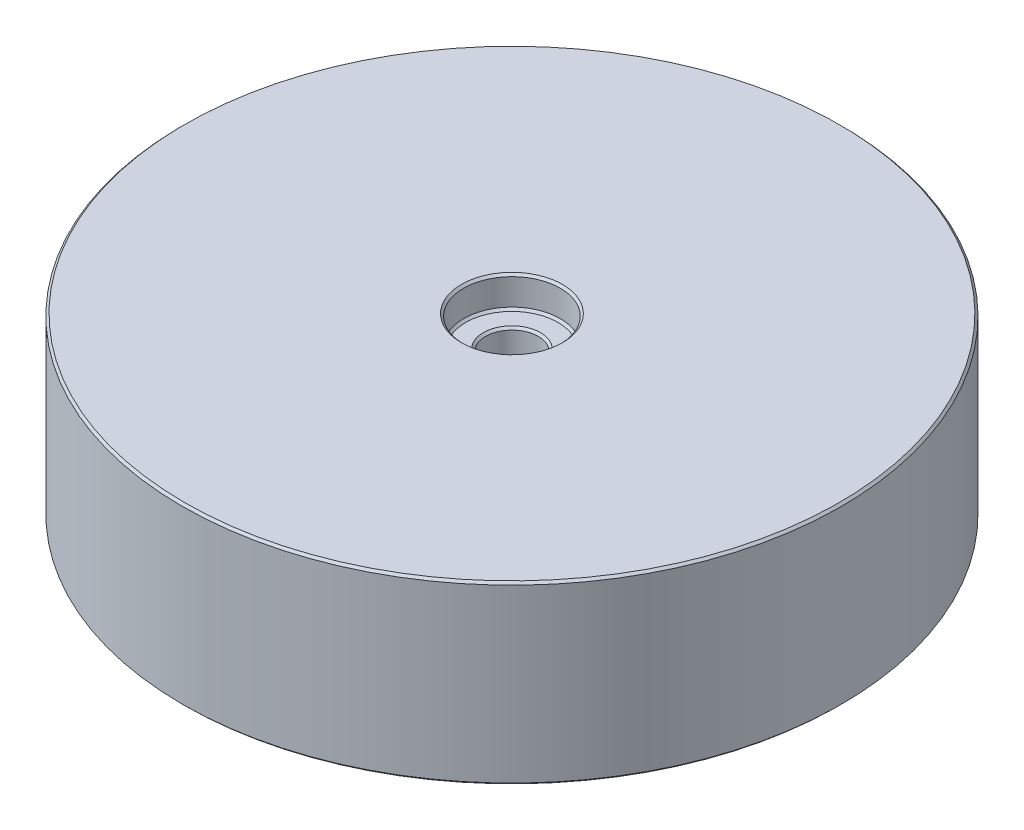
SolidWorks part; units mm, degrees
ref_plane "Front Plane" through (0, 0, 0) normal (0, 0, 1) x (1, 0, 0)
ref_plane "Top Plane" through (0, 0, 0) normal (0, 1, 0) x (1, 0, 0)
ref_plane "Right Plane" through (0, 0, 0) normal (1, 0, 0) x (0, 0, -1)
sketch "Sketch2" plane through (0, 0, 0) normal (1, 0, 0) x (0, 0, -1)
  line L0 (0, 77.6219) -> (0, -63.2806) construction
  line L1 (-6, 12.5) -> (-6, -12.5)
  line L2 (-11.5, -20) -> (-36.5, -20)
  line L3 (-37, -19.5) -> (-37, -10.5)
  line L4 (-37.5, -10) -> (-71.5, -10)
  line L5 (-72, -10.5) -> (-72, -19.5)
  line L6 (-72.5, -20) -> (-74.5, -20)
  line L7 (-75, -19.5) -> (-75, 19.5)
  line L8 (-74.5, 20) -> (-72.5, 20)
  line L9 (-72, 19.5) -> (-72, 10.5) construction
  line L10 (-71.5, 10) -> (-37.5, 10) construction
  line L11 (-37, 10.5) -> (-37, 19.5) construction
  line L12 (-36.5, 20) -> (-11.5, 20)
  line L13 (0, 0) -> (-86.9978, 0) construction
  line L14 (-6, -19.5) -> (-6.5, -20) construction
  line L15 (-6.5, 20) -> (-6, 19.5) construction
  line L16 (-36.5, -20) -> (-37, -19.5)
  line L17 (-37, 19.5) -> (-36.5, 20) construction
  line L18 (-72.5, 20) -> (-72, 19.5) construction
  line L19 (-72, 10.5) -> (-71.5, 10) construction
  line L20 (-37.5, 10) -> (-37, 10.5) construction
  line L21 (-75, 19.5) -> (-74.5, 20)
  line L22 (-74.5, -20) -> (-75, -19.5)
  line L23 (-72, -19.5) -> (-72.5, -20)
  line L24 (-71.5, -10) -> (-72, -10.5)
  line L25 (-37, -10.5) -> (-37.5, -10)
  line L26 (-11, 19.5) -> (-11, 13.5)
  line L27 (-10.5, 13) -> (-6.5, 13)
  line L28 (-6, 19.5) -> (-6, 13) construction
  line L29 (-11, 20) -> (-6.5, 20) construction
  line L30 (-10.5, -13) -> (-6.5, -13)
  line L31 (-11, -19.5) -> (-11, -13.5)
  line L32 (-6.5, -20) -> (-11, -20) construction
  line L33 (-6, -13) -> (-6, -19.5) construction
  line L34 (-6, -12.5) -> (-6.5, -13)
  line L35 (-11, -13.5) -> (-10.5, -13)
  line L36 (-11, -19.5) -> (-11.5, -20)
  line L37 (-11.5, 20) -> (-11, 19.5)
  line L38 (-11, 13.5) -> (-10.5, 13)
  line L39 (-6.5, 13) -> (-6, 12.5)
  line L40 (-72.5, 20) -> (-37, 20)
  line L41 (-37, 20) -> (-36.5, 20)
  point P2 (-6, 20)
  point P4 (-6, -20)
  point P6 (-37, -20)
  point P7 (-37, -10)
  point P8 (-72, -10)
  point P9 (-72, -20)
  point P10 (-75, -20)
  point P11 (-75, 20)
  point P12 (-72, 20)
  point P13 (-72, 10)
  point P14 (-37, 10)
  point P15 (-37, 20)
  point P42 (-11, 13)
  point P43 (-11, -13)
  dimension "D1" = 150
  dimension "D2" = 12
  dimension "D3" = 10
  dimension "D4" = 3
  dimension "D5" = 35
  dimension "D6" = 10
  dimension "D7" = 40
  dimension "D8" = 22
  dimension "D9" = 7
revolve "Revolve1" add sketch "Sketch2" angle 360 about L0
sketch "Sketch3" plane through (0, -10, 0) normal (0, -1, 0) x (1, 0, 0)
  line L0 (0, 0) -> (0, 79.0098) construction
  line L1 (41.0122, 55.8614) -> (20.5061, 35.3553) construction
  line L2 (-9.5, 69.5) -> (9.5, 69.5) construction
  line L3 (-10.5, 68.5) -> (-10.5, 39.5) construction
  line L4 (-9.5, 38.5) -> (9.5, 38.5) construction
  line L5 (10.5, 68.5) -> (10.5, 39.5) construction
  line L6 (-10.5, 69.5) -> (10.5, 38.5) construction
  line L7 (-10.5, 38.5) -> (10.5, 69.5) construction
  line L8 (42.4264, 55.8614) -> (55.8614, 42.4264) construction
  line L9 (55.8614, 41.0122) -> (35.3553, 20.5061) construction
  line L10 (20.5061, 33.9411) -> (33.9411, 20.5061) construction
  line L11 (68.5, 10.5) -> (39.5, 10.5) construction
  line L12 (69.5, 9.5) -> (69.5, -9.5) construction
  line L13 (68.5, -10.5) -> (39.5, -10.5) construction
  line L14 (38.5, 9.5) -> (38.5, -9.5) construction
  line L15 (55.8614, -41.0122) -> (35.3553, -20.5061) construction
  line L16 (55.8614, -42.4264) -> (42.4264, -55.8614) construction
  line L17 (41.0122, -55.8614) -> (20.5061, -35.3553) construction
  line L18 (33.9411, -20.5061) -> (20.5061, -33.9411) construction
  line L19 (10.5, -68.5) -> (10.5, -39.5) construction
  line L20 (9.5, -69.5) -> (-9.5, -69.5) construction
  line L21 (-10.5, -68.5) -> (-10.5, -39.5) construction
  line L22 (9.5, -38.5) -> (-9.5, -38.5) construction
  line L23 (-41.0122, -55.8614) -> (-20.5061, -35.3553) construction
  line L24 (-42.4264, -55.8614) -> (-55.8614, -42.4264) construction
  line L25 (-55.8614, -41.0122) -> (-35.3553, -20.5061) construction
  line L26 (-20.5061, -33.9411) -> (-33.9411, -20.5061) construction
  line L27 (-68.5, -10.5) -> (-39.5, -10.5) construction
  line L28 (-69.5, -9.5) -> (-69.5, 9.5) construction
  line L29 (-68.5, 10.5) -> (-39.5, 10.5) construction
  line L30 (-38.5, -9.5) -> (-38.5, 9.5) construction
  line L31 (-55.8614, 41.0122) -> (-35.3553, 20.5061) construction
  line L32 (-55.8614, 42.4264) -> (-42.4264, 55.8614) construction
  line L33 (-41.0122, 55.8614) -> (-20.5061, 35.3553) construction
  line L34 (-33.9411, 20.5061) -> (-20.5061, 33.9411) construction
  line L35 (0, 0) -> (0, 93.1932) construction
  circle A0 centre (0, 0) radius 71 construction
  circle A1 centre (0, 0) radius 71.5 construction
  circle A2 centre (0, 0) radius 38 construction
  circle A3 centre (0, 0) radius 37.5 construction
  arc A4 (10.5, 39.5) -> (9.5, 38.5) centre (9.5, 39.5) cw construction
  arc A5 (-10.5, 39.5) -> (-9.5, 38.5) centre (-9.5, 39.5) ccw construction
  arc A6 (10.5, 68.5) -> (9.5, 69.5) centre (9.5, 68.5) ccw construction
  arc A7 (-10.5, 68.5) -> (-9.5, 69.5) centre (-9.5, 68.5) cw construction
  arc A8 (41.0122, 55.8614) -> (42.4264, 55.8614) centre (41.7193, 55.1543) cw construction
  arc A9 (20.5061, 35.3553) -> (20.5061, 33.9411) centre (21.2132, 34.6482) ccw construction
  arc A10 (55.8614, 41.0122) -> (55.8614, 42.4264) centre (55.1543, 41.7193) ccw construction
  arc A11 (35.3553, 20.5061) -> (33.9411, 20.5061) centre (34.6482, 21.2132) cw construction
  arc A12 (68.5, 10.5) -> (69.5, 9.5) centre (68.5, 9.5) cw construction
  arc A13 (39.5, 10.5) -> (38.5, 9.5) centre (39.5, 9.5) ccw construction
  arc A14 (68.5, -10.5) -> (69.5, -9.5) centre (68.5, -9.5) ccw construction
  arc A15 (39.5, -10.5) -> (38.5, -9.5) centre (39.5, -9.5) cw construction
  arc A16 (55.8614, -41.0122) -> (55.8614, -42.4264) centre (55.1543, -41.7193) cw construction
  arc A17 (35.3553, -20.5061) -> (33.9411, -20.5061) centre (34.6482, -21.2132) ccw construction
  arc A18 (41.0122, -55.8614) -> (42.4264, -55.8614) centre (41.7193, -55.1543) ccw construction
  arc A19 (20.5061, -35.3553) -> (20.5061, -33.9411) centre (21.2132, -34.6482) cw construction
  arc A20 (10.5, -68.5) -> (9.5, -69.5) centre (9.5, -68.5) cw construction
  arc A21 (10.5, -39.5) -> (9.5, -38.5) centre (9.5, -39.5) ccw construction
  arc A22 (-10.5, -68.5) -> (-9.5, -69.5) centre (-9.5, -68.5) ccw construction
  arc A23 (-10.5, -39.5) -> (-9.5, -38.5) centre (-9.5, -39.5) cw construction
  arc A24 (-41.0122, -55.8614) -> (-42.4264, -55.8614) centre (-41.7193, -55.1543) cw construction
  arc A25 (-20.5061, -35.3553) -> (-20.5061, -33.9411) centre (-21.2132, -34.6482) ccw construction
  arc A26 (-55.8614, -41.0122) -> (-55.8614, -42.4264) centre (-55.1543, -41.7193) ccw construction
  arc A27 (-35.3553, -20.5061) -> (-33.9411, -20.5061) centre (-34.6482, -21.2132) cw construction
  arc A28 (-68.5, -10.5) -> (-69.5, -9.5) centre (-68.5, -9.5) cw construction
  arc A29 (-39.5, -10.5) -> (-38.5, -9.5) centre (-39.5, -9.5) ccw construction
  arc A30 (-68.5, 10.5) -> (-69.5, 9.5) centre (-68.5, 9.5) ccw construction
  arc A31 (-39.5, 10.5) -> (-38.5, 9.5) centre (-39.5, 9.5) cw construction
  arc A32 (-55.8614, 41.0122) -> (-55.8614, 42.4264) centre (-55.1543, 41.7193) cw construction
  arc A33 (-35.3553, 20.5061) -> (-33.9411, 20.5061) centre (-34.6482, 21.2132) ccw construction
  arc A34 (-41.0122, 55.8614) -> (-42.4264, 55.8614) centre (-41.7193, 55.1543) ccw construction
  arc A35 (-20.5061, 35.3553) -> (-20.5061, 33.9411) centre (-21.2132, 34.6482) cw construction
  circle A36 centre (0, 65) radius 1.5
  circle A37 centre (0, 44) radius 1.5
  circle A38 centre (31.1127, 31.1127) radius 1.5
  circle A39 centre (45.9619, 45.9619) radius 1.5
  circle A40 centre (44, 0) radius 1.5
  circle A41 centre (65, 0) radius 1.5
  circle A42 centre (31.1127, -31.1127) radius 1.5
  circle A43 centre (45.9619, -45.9619) radius 1.5
  circle A44 centre (0, -44) radius 1.5
  circle A45 centre (0, -65) radius 1.5
  circle A46 centre (-31.1127, -31.1127) radius 1.5
  circle A47 centre (-45.9619, -45.9619) radius 1.5
  circle A48 centre (-44, 0) radius 1.5
  circle A49 centre (-65, 0) radius 1.5
  circle A50 centre (-31.1127, 31.1127) radius 1.5
  circle A51 centre (-45.9619, 45.9619) radius 1.5
  point P9 (0, 54)
  point P112 (0, 0)
  point P116 (0, 38)
  point P117 (0, 71)
  point P149 (0, 0)
  dimension "D1" = 0.5
  dimension "D2" = 0.5
  dimension "D5" = 142
  dimension "D6" = 76
  dimension "D8" = 1
  dimension "D12" = 21
  dimension "D15" = 3
  dimension "D3" = 31
  dimension "D4" = 21
  dimension "D7" = 54
  dimension "D10" = 45
  dimension "D11" = 0
  dimension "D13" = 6
  dimension "D14" = 6
  dimension "D9" = 8
  dimension "D16" = 8
extrude "Cut-Extrude1" cut sketch "Sketch3" against normal blind 15 contours A51 | A50 | A38 | A39 | A49 | A48 | A47 | A46 | A44 | A45 | A42 | A43 | A40 | A41 | A37 | A36
sketch "Sketch4" plane through (0, -20, 0) normal (0, 1, 0) x (1, 0, 0)
  circle A0 centre (0, 0) radius 20.5
  circle A1 centre (0, 0) radius 14.5
  dimension "D1" = 41
  dimension "D2" = 29
extrude "Cut-Extrude2" cut sketch "Sketch4" along normal blind 10
chamfer "Chamfer1" distance 1 angle 45 2 edges at (0, -20, 20.5) (0, -20, 14.5)
